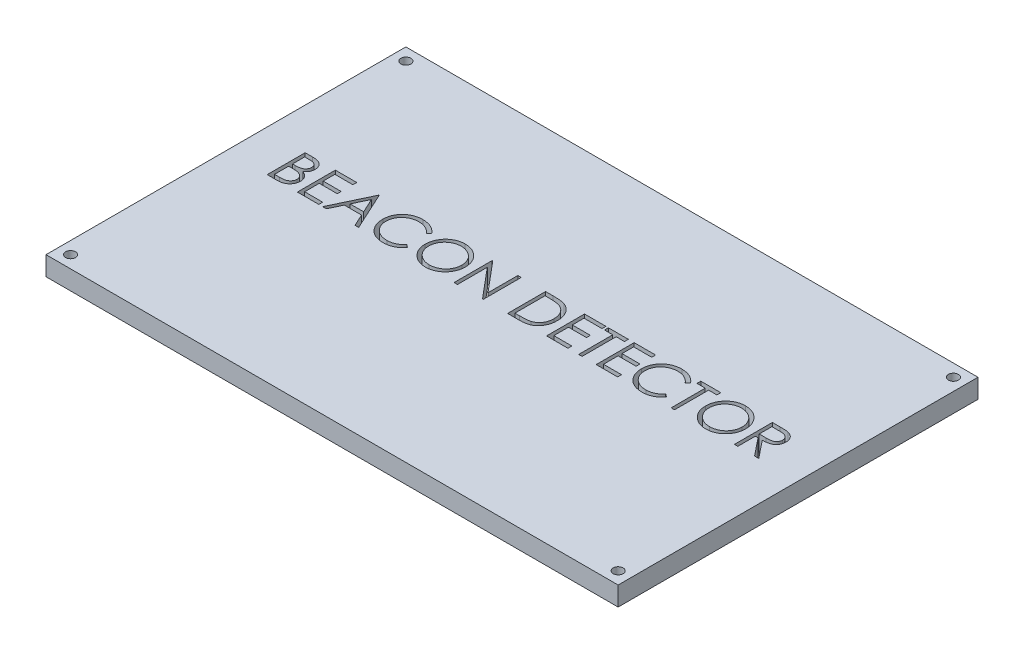
SolidWorks part; units mm, degrees
ref_plane "Front Plane" through (0, 0, 0) normal (0, 0, 1) x (1, 0, 0)
ref_plane "Top Plane" through (0, 0, 0) normal (0, 1, 0) x (1, 0, 0)
ref_plane "Right Plane" through (0, 0, 0) normal (1, 0, 0) x (0, 0, -1)
sketch "Sketch1" plane through (0, 0, 0) normal (0, 1, 0) x (1, 0, 0)
  line L1 (-133.7801, 59.9865) -> (25.7319, 59.9865)
  line L2 (-133.7801, 59.9865) -> (-133.7801, -40.3435)
  line L3 (-133.7801, -40.3435) -> (25.7319, -40.3435)
  line L4 (25.7319, 59.9865) -> (25.7319, -40.3435)
  dimension "D1" = 159.512
  dimension "D2" = 100.33
extrude "Boss-Extrude1" add sketch "Sketch1" along normal blind 5.334
sketch "Sketch2" plane through (0, 5.334, 0) normal (0, 1, 0) x (1, 0, 0)
  line L0 (25.7319, 59.9865) -> (-133.7801, 59.9865) construction
  line L1 (-133.7801, 59.9865) -> (-133.7801, -40.3435) construction
  line L2 (-54.0241, 59.9865) -> (-54.0241, -40.3435) construction
  line L3 (-133.7801, -40.3435) -> (25.7319, -40.3435) construction
  line L4 (-133.7801, 9.8215) -> (25.7319, 9.8215) construction
  line L5 (25.7319, -40.3435) -> (25.7319, 59.9865) construction
  circle A0 centre (-130.3511, 56.5575) radius 1.397
  circle A1 centre (22.3029, 56.5575) radius 1.397
  circle A2 centre (22.3029, -36.9145) radius 1.397
  circle A3 centre (-130.3511, -36.9145) radius 1.397
  dimension "D1" = 2.794
  dimension "D2" = 3.429
  dimension "D3" = 3.429
extrude "Cut-Extrude1" cut sketch "Sketch2" against normal through all
sketch "Sketch3" plane through (0, 5.334, 0) normal (0, 1, 0) x (1, 0, 0)
  line L0 (-133.7801, 9.8215) -> (25.7319, 9.8215) construction
  line L1 (-133.7801, 59.9865) -> (-133.7801, -40.3435) construction
  line L2 (25.7319, -40.3435) -> (25.7319, 59.9865) construction
  text T0 "BEACON DETECTOR\r\n" font "Century Gothic" height in points 40
extrude "Cut-Extrude2" cut sketch "Sketch3" against normal through all
equation "\"MDF\"= .21in"
equation "\"Foamcore\"= .13in"
equation "\"Gmaterial\"= \"MDF\""
equation "\"D1@Boss-Extrude1\"=\"MDF\""
